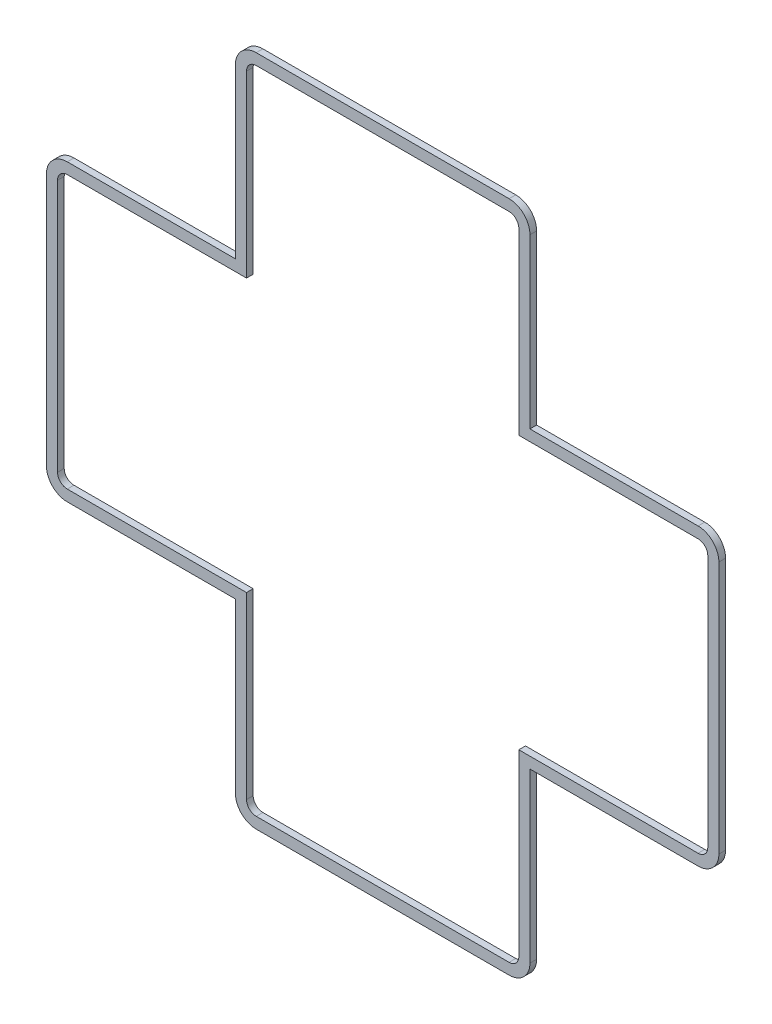
SolidWorks part; units mm, degrees
ref_plane "Alzado" through (0, 0, 0) normal (0, 0, 1) x (1, 0, 0)
ref_plane "Planta" through (0, 0, 0) normal (0, 1, 0) x (1, 0, 0)
ref_plane "Vista lateral" through (0, 0, 0) normal (1, 0, 0) x (0, 0, -1)
sketch "Croquis1" plane through (0, 0, 0) normal (0, 0, 1) x (1, 0, 0)
  line L0 (-283.764, 122.5) -> (-122.5, 122.5)
  line L1 (-283.764, 132.5) -> (-132.5, 132.5)
  line L2 (-132.5, 132.5) -> (-132.5, 283.764)
  line L3 (-122.5, 122.5) -> (-122.5, 283.764)
  line L4 (132.5, 283.764) -> (132.5, 132.5)
  line L5 (132.5, 132.5) -> (283.764, 132.5)
  line L6 (-113.764, 292.5) -> (113.764, 292.5)
  line L7 (283.764, -132.5) -> (132.5, -132.5)
  line L8 (132.5, -132.5) -> (132.5, -283.764)
  line L9 (-113.764, -302.5) -> (113.764, -302.5)
  line L10 (-132.5, -283.764) -> (-132.5, -132.5)
  line L11 (-283.764, -132.5) -> (-132.5, -132.5)
  line L12 (302.5, 113.764) -> (302.5, -113.764)
  line L13 (-302.5, 113.764) -> (-302.5, -113.764)
  line L14 (-113.764, 302.5) -> (113.764, 302.5)
  line L15 (122.5, 283.764) -> (122.5, 122.5)
  line L16 (122.5, 122.5) -> (283.764, 122.5)
  line L17 (292.5, 113.764) -> (292.5, -113.764)
  line L18 (283.764, -122.5) -> (122.5, -122.5)
  line L19 (122.5, -122.5) -> (122.5, -283.764)
  line L20 (-113.764, -292.5) -> (113.764, -292.5)
  line L21 (-122.5, -283.764) -> (-122.5, -122.5)
  line L22 (-283.764, -122.5) -> (-122.5, -122.5)
  line L23 (-292.5, 113.764) -> (-292.5, -113.764)
  arc A0 (-302.5, 113.764) -> (-283.764, 132.5) centre (-283.764, 113.764) cw
  arc A1 (-132.5, 283.764) -> (-113.764, 302.5) centre (-113.764, 283.764) cw
  arc A2 (113.764, 302.5) -> (132.5, 283.764) centre (113.764, 283.764) cw
  arc A3 (283.764, 132.5) -> (302.5, 113.764) centre (283.764, 113.764) cw
  arc A4 (302.5, -113.764) -> (283.764, -132.5) centre (283.764, -113.764) cw
  arc A5 (132.5, -283.764) -> (113.764, -302.5) centre (113.764, -283.764) cw
  arc A6 (-113.764, -302.5) -> (-132.5, -283.764) centre (-113.764, -283.764) cw
  arc A7 (-283.764, -132.5) -> (-302.5, -113.764) centre (-283.764, -113.764) cw
  arc A8 (-122.5, 283.764) -> (-113.764, 292.5) centre (-113.764, 283.764) cw
  arc A9 (113.764, 292.5) -> (122.5, 283.764) centre (113.764, 283.764) cw
  arc A10 (283.764, 122.5) -> (292.5, 113.764) centre (283.764, 113.764) cw
  arc A11 (292.5, -113.764) -> (283.764, -122.5) centre (283.764, -113.764) cw
  arc A12 (122.5, -283.764) -> (113.764, -292.5) centre (113.764, -283.764) cw
  arc A13 (-113.764, -292.5) -> (-122.5, -283.764) centre (-113.764, -283.764) cw
  arc A14 (-283.764, -122.5) -> (-292.5, -113.764) centre (-283.764, -113.764) cw
  arc A15 (-292.5, 113.764) -> (-283.764, 122.5) centre (-283.764, 113.764) cw
  point P2 (-302.5, 132.5)
  point P8 (-132.5, 302.5)
  point P14 (132.5, 302.5)
  point P18 (302.5, 132.5)
  point P33 (-302.5, -132.5)
  dimension "D5" = 265
  dimension "D7" = 18.736
  dimension "D8" = 18.736
  dimension "D1" = 170
  dimension "D2" = 170
  dimension "D3" = 170
  dimension "D4" = 170
  dimension "D6" = 265
  dimension "D9" = 302.5
  dimension "D10" = 302.5
  dimension "D11" = 10
extrude "Saliente-Extruir1" add sketch "Croquis1" along normal blind 6
sketch "Croquis2" plane through (0, 0, 6) normal (0, 0, 1) x (1, 0, 0)
  line L0 (-122.5, 122.5) -> (-132.5, 132.5) construction
  line L1 (0, 292.5) -> (0, 302.5) construction
  line L2 (113.764, 292.5) -> (-113.764, 292.5) construction
  line L3 (113.764, 302.5) -> (-113.764, 302.5) construction
  line L4 (0, 302.5) -> (-113.764, 302.5)
  line L5 (-132.5, 283.764) -> (-132.5, 132.5)
  line L6 (-132.5, 132.5) -> (-122.5, 122.5)
  line L7 (-122.5, 122.5) -> (-122.5, 283.764)
  line L8 (-113.764, 292.5) -> (0, 292.5)
  line L9 (0, 292.5) -> (0, 302.5)
  arc A0 (-113.764, 302.5) -> (-132.5, 283.764) centre (-113.764, 283.764) ccw
  arc A1 (-122.5, 283.764) -> (-113.764, 292.5) centre (-113.764, 283.764) cw
